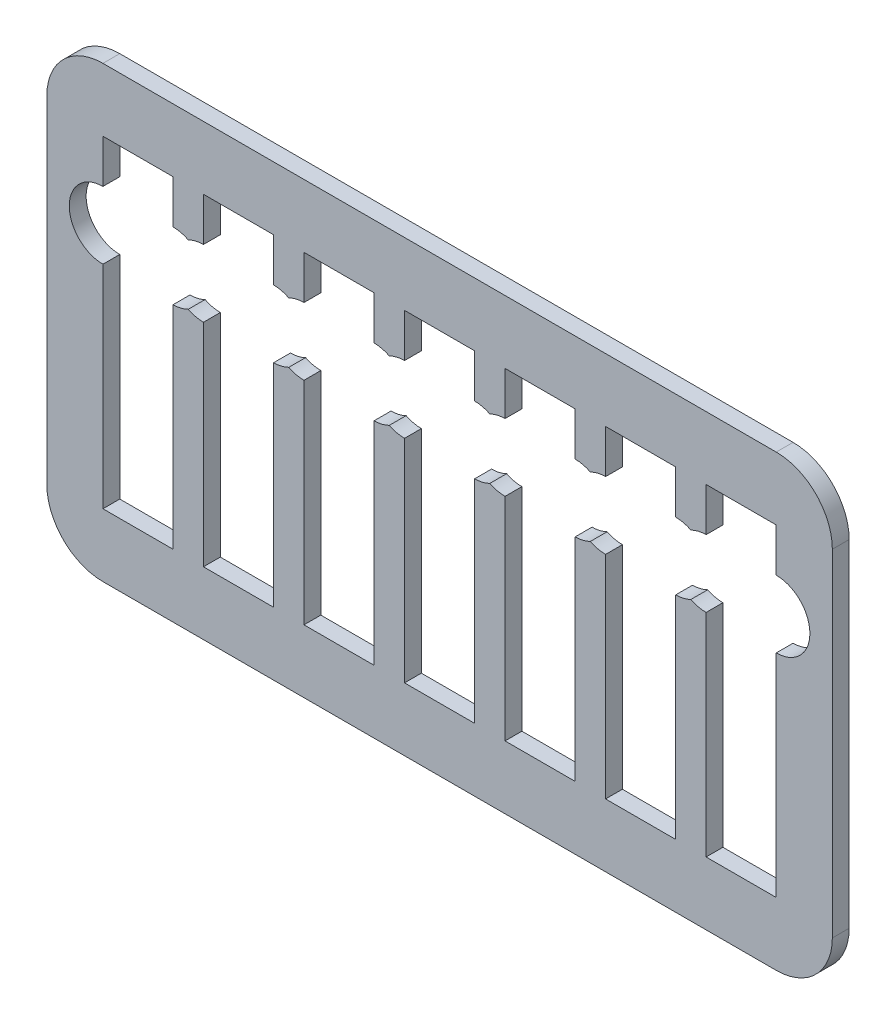
SolidWorks part; units mm, degrees
ref_plane "Front Plane" through (0, 0, 0) normal (0, 0, 1) x (1, 0, 0)
ref_plane "Top Plane" through (0, 0, 0) normal (0, 1, 0) x (1, 0, 0)
ref_plane "Right Plane" through (0, 0, 0) normal (1, 0, 0) x (0, 0, -1)
sketch "Sketch1" plane through (0, 0, 0) normal (0, 0, 1) x (1, 0, 0)
  line L1 (20, 0) -> (260, 0)
  line L2 (0, 20) -> (0, 140)
  line L3 (20, 160) -> (260, 160)
  line L4 (280, 20) -> (280, 140)
  arc A0 (260, 0) -> (280, 20) centre (260, 20) ccw
  arc A1 (260, 160) -> (280, 140) centre (260, 140) cw
  arc A2 (0, 140) -> (20, 160) centre (20, 140) cw
  arc A3 (20, 0) -> (0, 20) centre (20, 20) cw
  point P7 (280, 0)
  point P10 (280, 160)
  point P13 (0, 160)
  point P16 (0, 0)
  dimension "D3" = 20
  dimension "D1" = 280
  dimension "D2" = 160
extrude "Boss-Extrude1" add sketch "Sketch1" along normal blind 6
sketch "Sketch2" plane through (0, 0, 6) normal (0, 0, 1) x (1, 0, 0)
  line L0 (20, 137.5) -> (20, 160) construction
  line L1 (20, 137.5) -> (45, 137.5)
  line L2 (20, 137.5) -> (20, 122)
  line L3 (20, 22.5) -> (45, 22.5)
  line L4 (45, 137.5) -> (45, 122)
  line L5 (260, 160) -> (20, 160) construction
  line L6 (20, 22.5) -> (20, 0) construction
  line L8 (0, 110) -> (280, 110) construction
  line L11 (32.5, 22.5) -> (32.5, 37.2302) construction
  line L12 (20, 98) -> (20, 22.5)
  line L13 (45, 98) -> (45, 22.5)
  line L14 (55.8333, 137.5) -> (55.8333, 122)
  line L15 (55.8333, 98) -> (55.8333, 22.5)
  line L16 (55.8333, 22.5) -> (80.8333, 22.5)
  line L17 (80.8333, 98) -> (80.8333, 22.5)
  line L18 (80.8333, 137.5) -> (80.8333, 122)
  line L19 (55.8333, 137.5) -> (80.8333, 137.5)
  line L20 (91.6667, 137.5) -> (91.6667, 122)
  line L21 (91.6667, 98) -> (91.6667, 22.5)
  line L22 (91.6667, 22.5) -> (116.6667, 22.5)
  line L23 (116.6667, 98) -> (116.6667, 22.5)
  line L24 (116.6667, 137.5) -> (116.6667, 122)
  line L25 (91.6667, 137.5) -> (116.6667, 137.5)
  line L26 (127.5, 137.5) -> (127.5, 122)
  line L27 (127.5, 98) -> (127.5, 22.5)
  line L28 (127.5, 22.5) -> (152.5, 22.5)
  line L29 (152.5, 98) -> (152.5, 22.5)
  line L30 (152.5, 137.5) -> (152.5, 122)
  line L31 (127.5, 137.5) -> (152.5, 137.5)
  line L32 (163.3333, 137.5) -> (163.3333, 122)
  line L33 (163.3333, 98) -> (163.3333, 22.5)
  line L34 (163.3333, 22.5) -> (188.3333, 22.5)
  line L35 (188.3333, 98) -> (188.3333, 22.5)
  line L36 (188.3333, 137.5) -> (188.3333, 122)
  line L37 (163.3333, 137.5) -> (188.3333, 137.5)
  line L38 (199.1667, 137.5) -> (199.1667, 122)
  line L39 (199.1667, 98) -> (199.1667, 22.5)
  line L40 (199.1667, 22.5) -> (224.1667, 22.5)
  line L41 (224.1667, 98) -> (224.1667, 22.5)
  line L42 (224.1667, 137.5) -> (224.1667, 122)
  line L43 (199.1667, 137.5) -> (224.1667, 137.5)
  line L44 (235, 137.5) -> (235, 122)
  line L45 (235, 98) -> (235, 22.5)
  line L46 (235, 22.5) -> (260, 22.5)
  line L47 (260, 98) -> (260, 22.5)
  line L48 (260, 137.5) -> (260, 122)
  line L49 (235, 137.5) -> (260, 137.5)
  line L50 (20, 44.6954) -> (0, 44.6954) construction
  line L51 (0, 140) -> (0, 20) construction
  line L52 (260, 44.6954) -> (280, 44.6954) construction
  line L53 (280, 20) -> (280, 140) construction
  arc A0 (45, 122) -> (50.4167, 120.7079) centre (45, 110) cw
  arc A1 (20, 122) -> (20, 98) centre (20, 110) ccw
  arc A2 (55.8333, 122) -> (50.4167, 120.7079) centre (55.8333, 110) ccw
  arc A3 (80.8333, 122) -> (86.25, 120.7079) centre (80.8333, 110) cw
  arc A4 (91.6667, 122) -> (86.25, 120.7079) centre (91.6667, 110) ccw
  arc A5 (116.6667, 122) -> (122.0833, 120.7079) centre (116.6667, 110) cw
  arc A6 (127.5, 122) -> (122.0833, 120.7079) centre (127.5, 110) ccw
  arc A7 (152.5, 122) -> (157.9167, 120.7079) centre (152.5, 110) cw
  arc A8 (163.3333, 122) -> (157.9167, 120.7079) centre (163.3333, 110) ccw
  arc A9 (188.3333, 122) -> (193.75, 120.7079) centre (188.3333, 110) cw
  arc A10 (199.1667, 122) -> (193.75, 120.7079) centre (199.1667, 110) ccw
  arc A11 (224.1667, 122) -> (229.5833, 120.7079) centre (224.1667, 110) cw
  arc A12 (235, 122) -> (229.5833, 120.7079) centre (235, 110) ccw
  arc A13 (260, 122) -> (260, 98) centre (260, 110) cw
  arc A14 (50.4167, 99.2921) -> (55.8333, 98) centre (55.8333, 110) ccw
  arc A15 (50.4167, 99.2921) -> (45, 98) centre (45, 110) cw
  arc A16 (86.25, 99.2921) -> (80.8333, 98) centre (80.8333, 110) cw
  arc A17 (86.25, 99.2921) -> (91.6667, 98) centre (91.6667, 110) ccw
  arc A18 (122.0833, 99.2921) -> (127.5, 98) centre (127.5, 110) ccw
  arc A19 (122.0833, 99.2921) -> (116.6667, 98) centre (116.6667, 110) cw
  arc A20 (157.9167, 99.2921) -> (163.3333, 98) centre (163.3333, 110) ccw
  arc A21 (157.9167, 99.2921) -> (152.5, 98) centre (152.5, 110) cw
  arc A22 (193.75, 99.2921) -> (199.1667, 98) centre (199.1667, 110) ccw
  arc A23 (193.75, 99.2921) -> (188.3333, 98) centre (188.3333, 110) cw
  arc A24 (229.5833, 99.2921) -> (224.1667, 98) centre (224.1667, 110) cw
  arc A25 (229.5833, 99.2921) -> (235, 98) centre (235, 110) ccw
  dimension "D3" = 12
  dimension "D1" = 25
  dimension "D2" = 115
  dimension "D4" = 50
  dimension "D5" = 7
extrude "Cut-Extrude1" cut sketch "Sketch2" against normal blind 6
